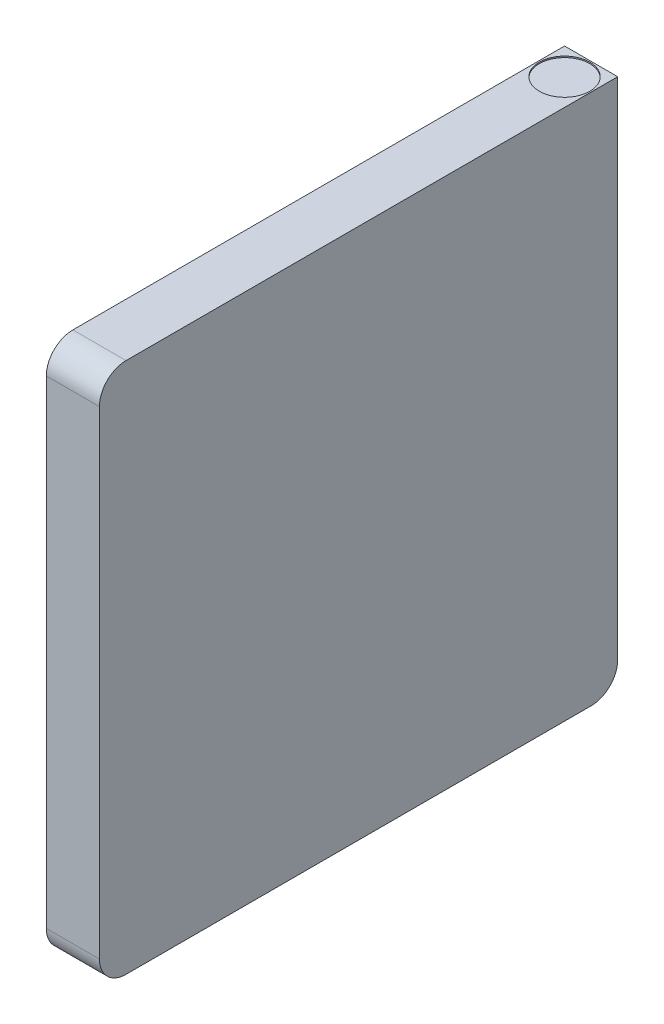
SolidWorks part; units mm, degrees
ref_plane "Front Plane" through (0, 0, 0) normal (0, 0, 1) x (1, 0, 0)
ref_plane "Top Plane" through (0, 0, 0) normal (0, 1, 0) x (1, 0, 0)
ref_plane "Right Plane" through (0, 0, 0) normal (1, 0, 0) x (0, 0, -1)
sketch "Sketch1" plane through (0, 0, 0) normal (0, 0, 1) x (1, 0, 0)
  line L1 (-4, 25.4908) -> (0, 25.4908)
  line L2 (-4, 25.4908) -> (-4, -14.5092)
  line L3 (-4, -14.5092) -> (0, -14.5092)
  line L4 (0, 25.4908) -> (0, -14.5092)
  dimension "D1" = 40
  dimension "D2" = 4
extrude "Boss-Extrude1" add sketch "Sketch1" along normal blind 39
ref_plane "Plane1" through (0, 0, 0) normal (1, 0, 0) x (0, 0, -1)
fillet "Fillet6" radius 2 1 edges at (-2, 25.4908, 39)
fillet "Fillet7" radius 2 2 edges at (-2, -14.5092, 0) (-2, -14.5092, 39)
sketch "Sketch7" plane through (0, 25.4908, 0) normal (0, 1, 0) x (1, 0, 0)
  circle A1 centre (-2, -2) radius 1.9
extrude "Cut-Extrude4" cut sketch "Sketch7" against normal blind 0.1
